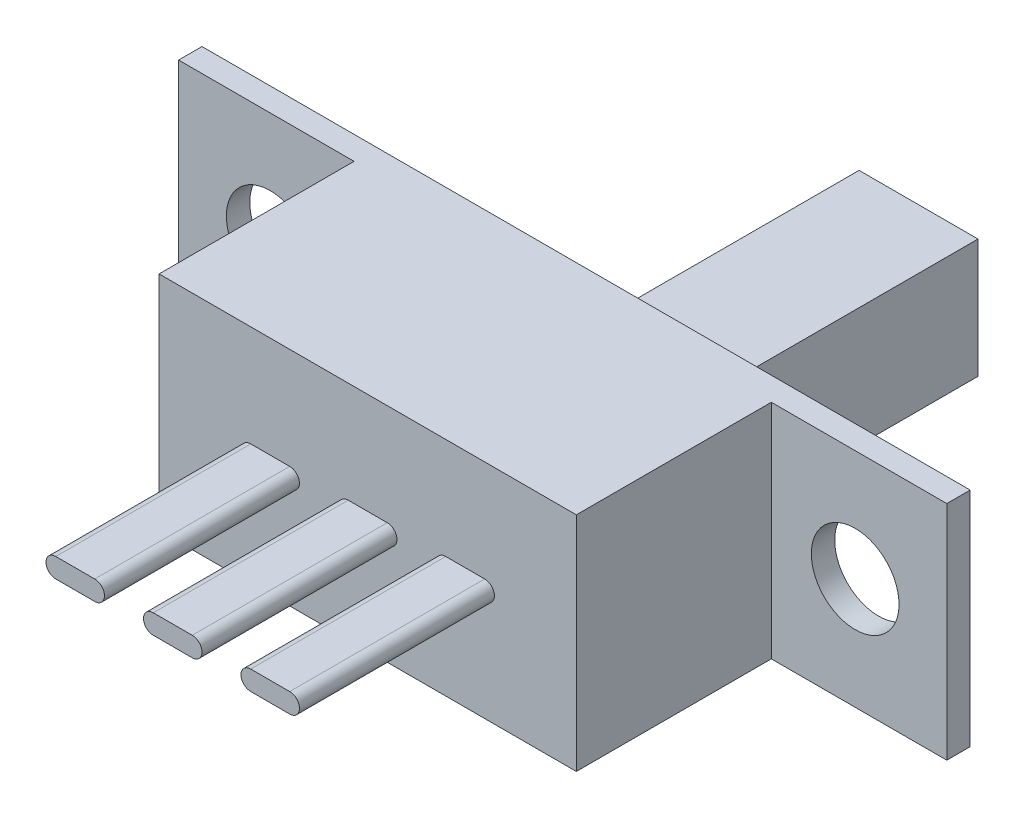
SolidWorks part; units mm, degrees
ref_plane "Front" through (0, 0, 0) normal (0, 0, 1) x (1, 0, 0)
ref_plane "Top" through (0, 0, 0) normal (0, 1, 0) x (1, 0, 0)
ref_plane "Right" through (0, 0, 0) normal (1, 0, 0) x (0, 0, -1)
sketch "Sketch1" plane through (0, 0, 0) normal (0, 0, 1) x (1, 0, 0)
  line L0 (10, -89.5) -> (9.85, -89.5) construction
  line L1 (10, -92.5) -> (10, -86.5) construction
  line L2 (-10, -89.5) -> (-9.85, -89.5) construction
  line L3 (-10, -86.5) -> (-10, -92.5) construction
  line L5 (9.85, -92.35) -> (-9.85, -92.35)
  line L6 (9.85, -92.35) -> (9.85, -86.65)
  line L7 (9.85, -86.65) -> (-9.85, -86.65)
  line L8 (-9.85, -92.35) -> (-9.85, -86.65)
  circle A0 centre (7.5, -89.5) radius 1.125
  circle A1 centre (-7.5, -89.5) radius 1.125
  dimension "D3" = 2.25
  dimension "D1" = 5.7
  dimension "D2" = 19.7
extrude "Boss-Extrude1" add sketch "Sketch1" along normal blind 0.6
sketch "Sketch2" plane through (0, 0, 0.6) normal (0, 0, 1) x (1, 0, 0)
  line L0 (9.85, -86.65) -> (-9.85, -86.65) construction
  line L1 (-5.35, -86.65) -> (5.35, -86.65)
  line L2 (-5.35, -86.65) -> (-5.35, -92.35)
  line L3 (-5.35, -92.35) -> (5.35, -92.35)
  line L4 (5.35, -86.65) -> (5.35, -92.35)
  line L5 (-9.85, -92.35) -> (9.85, -92.35) construction
  line L6 (-7.5, -89.5) -> (-5.35, -89.5) construction
  line L7 (7.5, -89.5) -> (5.35, -89.5) construction
  dimension "D1" = 10.7
extrude "Boss-Extrude2" add sketch "Sketch2" along normal blind 5
sketch "Sketch3" plane through (0, 0, 0) normal (0, 0, -1) x (-1, 0, 0)
  line L0 (-10, -89.5) -> (-9.85, -89.5) construction
  line L1 (-3.05, -87.975) -> (0, -87.975)
  line L2 (-3.05, -87.975) -> (-3.05, -91.025)
  line L3 (-3.05, -91.025) -> (0, -91.025)
  line L4 (0, -87.975) -> (0, -91.025)
  line L5 (-9.85, -92.35) -> (-9.85, -86.65) construction
  point P4 (-3.05, -89.5)
  dimension "D1" = 3.05
  dimension "D2" = 6.8
extrude "Boss-Extrude3" add sketch "Sketch3" along normal blind 7
sketch "Sketch4" plane through (0, 0, 5.6) normal (0, 0, 1) x (1, 0, 0)
  line L0 (-0.5, -89.5) -> (0.5, -89.5) construction
  line L1 (-0.5, -89.25) -> (0.5, -89.25)
  line L2 (-0.5, -89.75) -> (0.5, -89.75)
  line L3 (2, -89.5) -> (3, -89.5) construction
  line L4 (2, -89.25) -> (3, -89.25)
  line L5 (2, -89.75) -> (3, -89.75)
  line L6 (-3, -89.5) -> (-2, -89.5) construction
  line L7 (-3, -89.25) -> (-2, -89.25)
  line L8 (-3, -89.75) -> (-2, -89.75)
  line L10 (-7.5, -89.5) -> (0, -89.5) construction
  line L11 (0, -89.5) -> (7.5, -89.5) construction
  arc A0 (-0.5, -89.25) -> (-0.5, -89.75) centre (-0.5, -89.5) ccw
  arc A1 (0.5, -89.75) -> (0.5, -89.25) centre (0.5, -89.5) ccw
  arc A2 (2, -89.25) -> (2, -89.75) centre (2, -89.5) ccw
  arc A3 (3, -89.75) -> (3, -89.25) centre (3, -89.5) ccw
  arc A4 (-3, -89.25) -> (-3, -89.75) centre (-3, -89.5) ccw
  arc A5 (-2, -89.75) -> (-2, -89.25) centre (-2, -89.5) ccw
  point P2 (0, -89.5)
  point P8 (2.5, -89.5)
  point P15 (-2.5, -89.5)
  dimension "D1" = 1.5
  dimension "D2" = 0.5
  dimension "D3" = 2.5
  dimension "D4" = 2.5
extrude "Boss-Extrude4" add sketch "Sketch4" along normal blind 5
